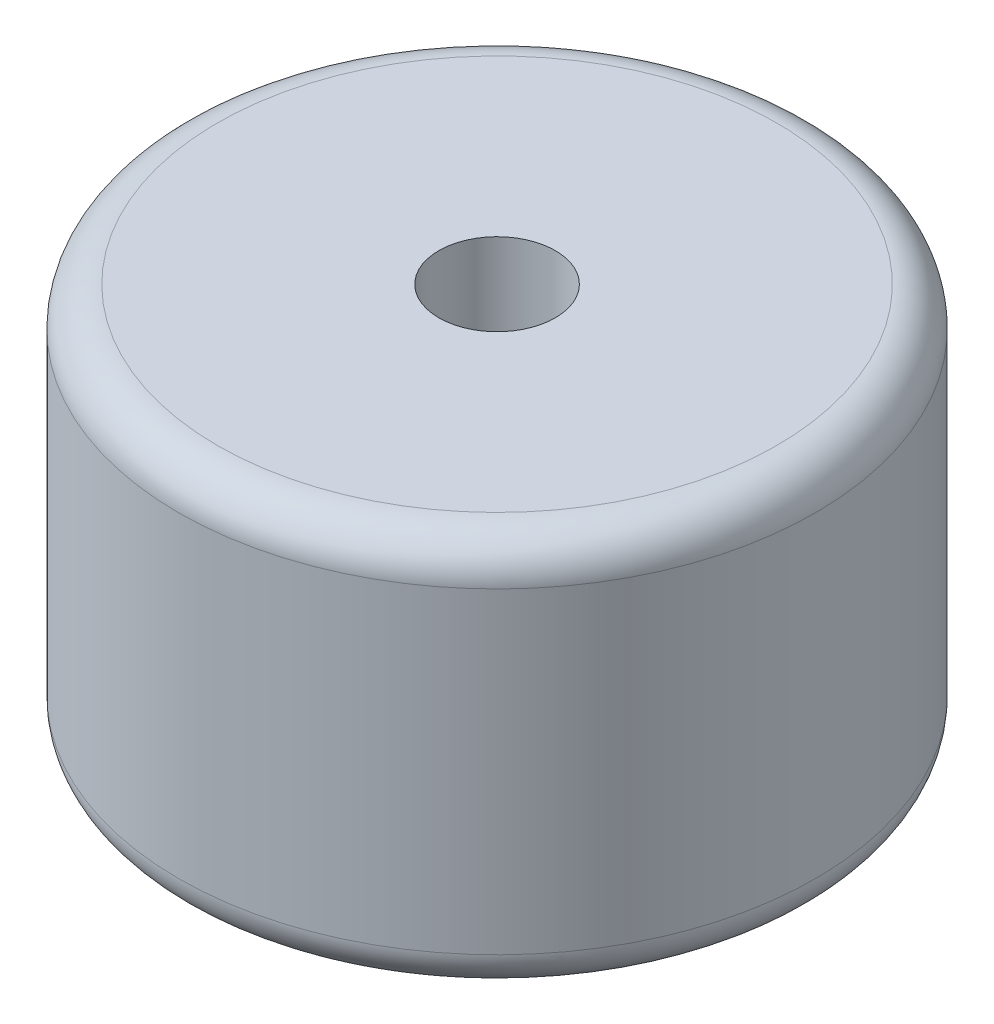
SolidWorks part; units mm, degrees
ref_plane "Front Plane" through (0, 0, 0) normal (0, 0, 1) x (1, 0, 0)
ref_plane "Top Plane" through (0, 0, 0) normal (0, 1, 0) x (1, 0, 0)
ref_plane "Right Plane" through (0, 0, 0) normal (1, 0, 0) x (0, 0, -1)
sketch "Sketch1" plane through (0, 0, 0) normal (0, 1, 0) x (1, 0, 0)
  circle A0 centre (0, 0) radius 41
  dimension "D1" = 82
extrude "Boss-Extrude1" add sketch "Sketch1" along normal mid plane 50.8
fillet "Fillet1" radius 5 2 edges at (0, -25.4, 41) (0, 25.4, 41)
sketch "Sketch2" plane through (0, 25.4, 0) normal (0, 1, 0) x (1, 0, 0)
  circle A0 centre (0, 0) radius 7.5
  dimension "D1" = 15
extrude "Cut-Extrude1" cut sketch "Sketch2" against normal through all both and the other way through all
